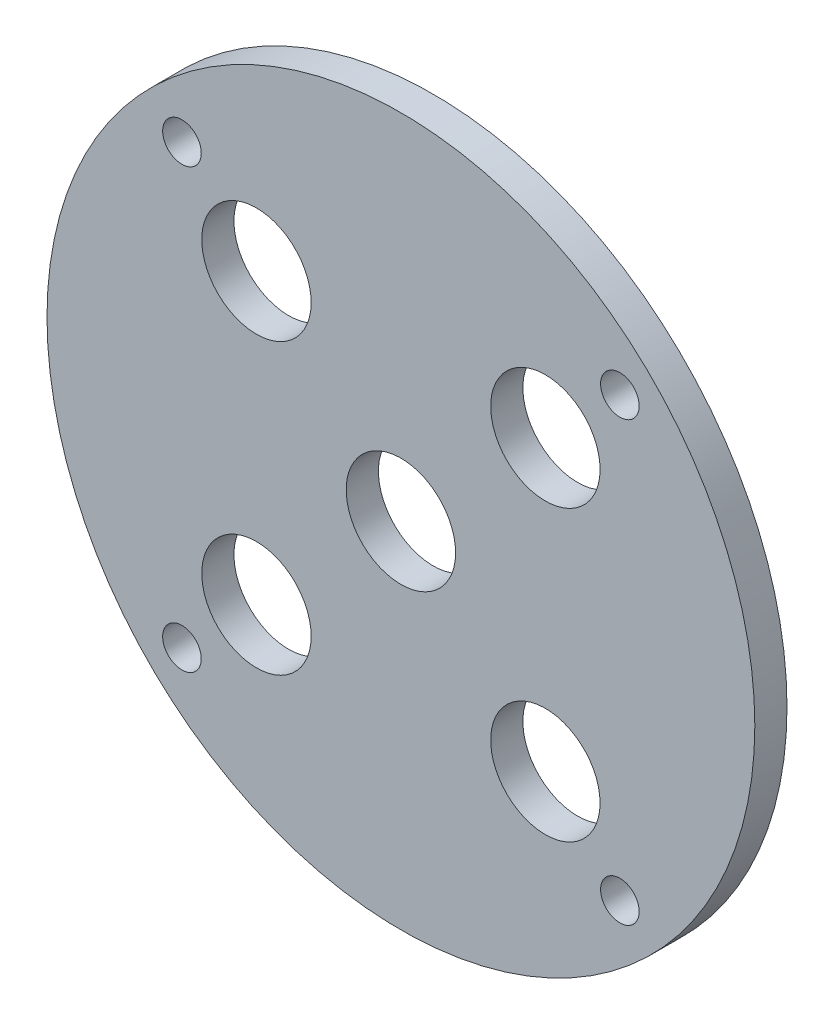
SolidWorks part; units mm, degrees
material "ABS"
ref_plane "Front Plane" through (0, 0, 0) normal (0, 0, 1) x (1, 0, 0)
ref_plane "Top Plane" through (0, 0, 0) normal (0, 1, 0) x (1, 0, 0)
ref_plane "Right Plane" through (0, 0, 0) normal (1, 0, 0) x (0, 0, -1)
sketch "Sketch2" plane through (0, 0, 0) normal (0, 0, 1) x (1, 0, 0)
  line L0 (4.4901, 4.49) -> (7.7782, 7.7781)
  circle A0 centre (-4.4901, 4.49) radius 1.7
  circle A1 centre (4.4901, 4.49) radius 1.7
  circle A2 centre (-4.4901, -4.4902) radius 1.7
  circle A3 centre (4.4901, -4.4902) radius 1.7
  circle A4 centre (0, -0.0001) radius 11
  circle A6 centre (0, -0.0001) radius 1.7
  circle A7 centre (6.8055, 6.8054) radius 0.6
  circle A8 centre (6.8054, -6.8055) radius 0.6
  circle A9 centre (-6.8055, -6.8054) radius 0.6
  circle A10 centre (-6.8054, 6.8055) radius 0.6
  point P15 (0, -0.2001)
  point P16 (11, -0.0001)
  point P17 (11, -0.2001)
  point P18 (0, 0.1999)
  point P19 (11, 0.1999)
  point P21 (0.3536, -0.3536)
  point P23 (8.2902, 7.6918)
  point P24 (-0.3536, 0.3535)
  point P25 (7.6108, 8.2892)
  point P36 (0, 0)
  point P43 (0, 0)
  dimension "D1" = 22
  dimension "D4" = 4
  dimension "D3" = 3.4
  dimension "D5" = 3.4
  dimension "D6" = 3.4
  dimension "D7" = 3.4
  dimension "D8" = 3.4
  dimension "D2" = 1.2
extrude "Boss-Extrude1" add sketch "Sketch2" along normal blind 1
